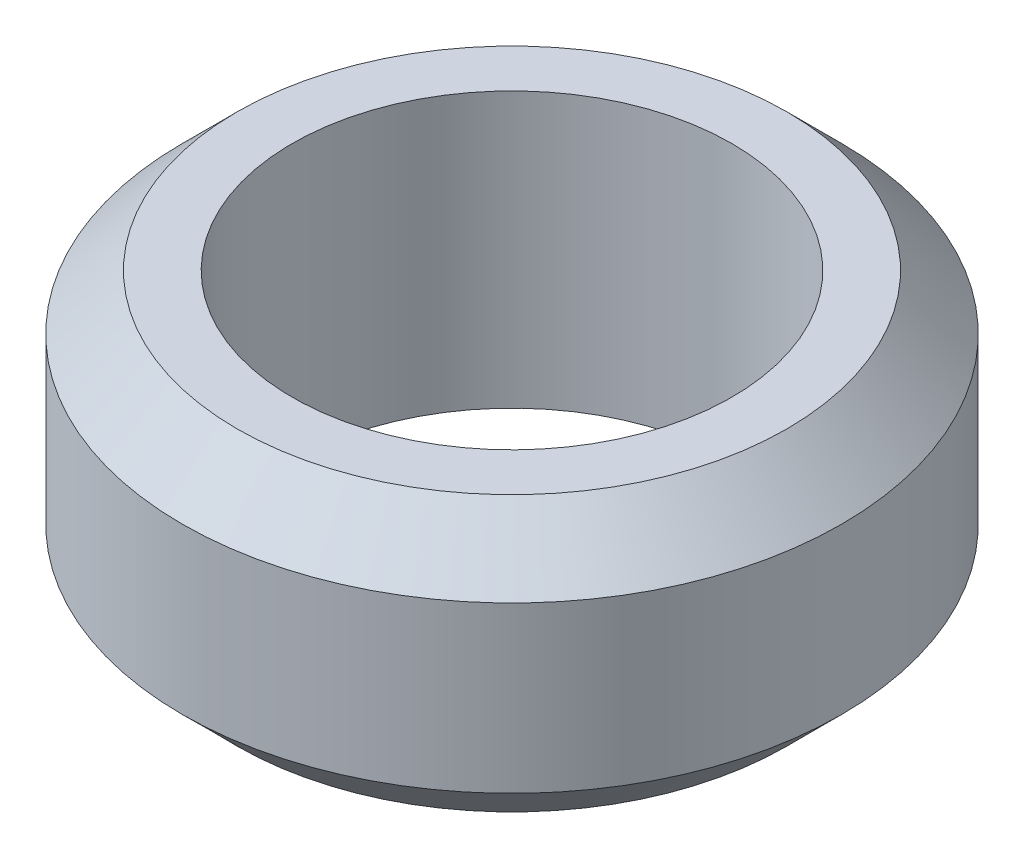
SolidWorks part; units mm, degrees
ref_plane "Front Plane" through (0, 0, 0) normal (0, 0, 1) x (1, 0, 0)
ref_plane "Top Plane" through (0, 0, 0) normal (0, 1, 0) x (1, 0, 0)
ref_plane "Right Plane" through (0, 0, 0) normal (1, 0, 0) x (0, 0, -1)
sketch "Sketch1" plane through (0, 0, 0) normal (0, 0, 1) x (1, 0, 0)
  line L0 (0, 0) -> (0, 19.5053) construction
  line L5 (8, 0) -> (12, 0)
  line L6 (8, 0) -> (8, 5)
  line L7 (8, 5) -> (12, 5)
  line L8 (12, 0) -> (12, 5)
  line L9 (0, 0) -> (36.6916, 0) construction
  line L10 (10, 5) -> (12, 3)
  dimension "D1" = 5
  dimension "D2" = 16
  dimension "D3" = 24
  dimension "D4" = 45
  dimension "D5" = 20
revolve "Revolve2" add sketch "Sketch1" angle 360 about L0
mirror "Mirror1" about plane through (0, 0, 0) normal (0, -1, 0) of "Revolve2"
